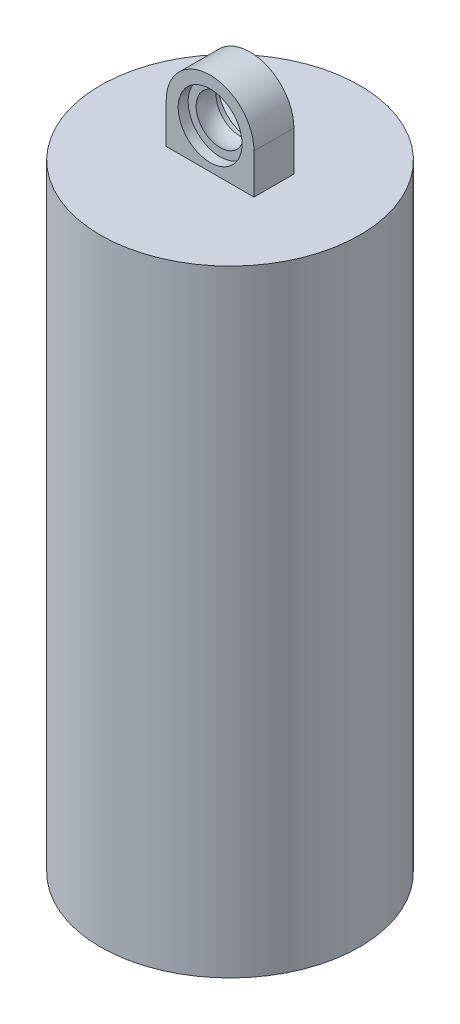
SolidWorks part; units mm, degrees
ref_plane "前视基准面" through (0, 0, 0) normal (0, 0, 1) x (1, 0, 0)
ref_plane "上视基准面" through (0, 0, 0) normal (0, 1, 0) x (1, 0, 0)
ref_plane "右视基准面" through (0, 0, 0) normal (1, 0, 0) x (0, 0, -1)
sketch "草图1" plane through (0, 0, 0) normal (0, 1, 0) x (1, 0, 0)
  circle A0 centre (0, 0) radius 32.5
  dimension "D1" = 65
extrude "凸台-拉伸1" add sketch "草图1" along normal blind 154.5
sketch "草图2" plane through (0, 0, 0) normal (0, -1, 0) x (1, 0, 0)
  circle A0 centre (0, 0) radius 12.5
  dimension "D1" = 25
extrude "凸台-拉伸2" add sketch "草图2" along normal blind 6
sketch "草图3" plane through (0, -6, 0) normal (0, -1, 0) x (1, 0, 0)
  circle A0 centre (0, 0) radius 6
  dimension "D1" = 12
extrude "切除-拉伸1" cut sketch "草图3" against normal blind 80
sketch "草图4" plane through (0, 0, 0) normal (0, 0, 1) x (1, 0, 0)
  line L0 (32.5, 154.5) -> (-32.5, 154.5) construction
  line L1 (-11, 154.5) -> (11, 154.5)
  line L2 (-11, 154.5) -> (-11, 164.5)
  line L4 (11, 154.5) -> (11, 164.5)
  line L5 (0, 193.283) -> (0, 138.3299) construction
  arc A0 (-11, 164.5) -> (11, 164.5) centre (0, 164.5) cw
  circle A1 centre (0, 164.5) radius 8
  dimension "D4" = 16
  dimension "D5" = 10
  dimension "D1" = 22
  dimension "D2" = 11
  dimension "D3" = 10
extrude "凸台-拉伸3" add sketch "草图4" against normal mid plane 10
sketch "草图5" plane through (0, 0, 0) normal (0, 0, 1) x (1, 0, 0)
  circle A0 centre (0, 164.5) radius 8
extrude "凸台-拉伸4" add sketch "草图5" along normal mid plane 5
ref_plane "基准面4" through (0, 0, 4.5) normal (0, 0, 1) x (1, 0, 0)
sketch "草图7" plane through (0, 0, 2.5) normal (0, 0, 1) x (1, 0, 0)
  circle A0 centre (0, 164.5) radius 6
  dimension "D1" = 12
sketch "草图8" plane through (0, 0, 4.5) normal (0, 0, 1) x (1, 0, 0)
  circle A0 centre (0, 164.5) radius 4
  dimension "D1" = 8
loft "放样1" add profiles "草图8", "草图7"
mirror "镜向1" about plane through (0, 0, 0) normal (0, 0, 1) of "放样1"
sketch "草图9" plane through (0, 0, 4.5) normal (0, 0, 1) x (1, 0, 0)
  circle A0 centre (0, 166.7613) radius 2.5
  dimension "D1" = 5
extrude "切除-拉伸2" cut sketch "草图9" against normal blind 31
sketch "草图10" plane through (0, 0, 4.5) normal (0, 0, 1) x (1, 0, 0)
  circle A0 centre (0, 164.5) radius 6
  circle A4 centre (0, 164.5) radius 8 construction
extrude "切除-拉伸3" cut sketch "草图10" against normal blind 17
sketch "草图11" plane through (0, 0, 0) normal (0, 0, 1) x (1, 0, 0)
  line L0 (0, 171) -> (0, 158)
  arc A0 (0, 158) -> (0, 171) centre (0, 164.5) ccw
  dimension "D1" = 13
revolve "切除-旋转1" cut sketch "草图11" angle 360 about L0
